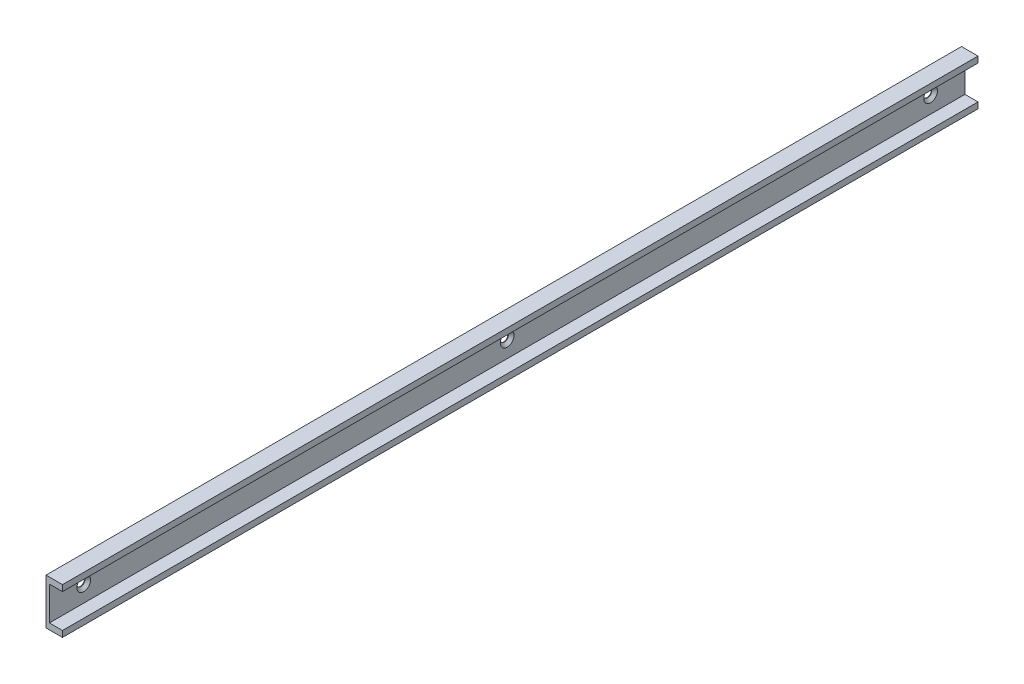
SolidWorks part; units mm, degrees
material "6061 合金"
ref_plane "前视基准面" through (0, 0, 0) normal (0, 0, 1) x (1, 0, 0)
ref_plane "上视基准面" through (0, 0, 0) normal (0, 1, 0) x (1, 0, 0)
ref_plane "右视基准面" through (0, 0, 0) normal (1, 0, 0) x (0, 0, -1)
sketch "草图1" plane through (0, 0, 0) normal (0, 0, 1) x (1, 0, 0)
  line L1 (-3.6, -10) -> (3.6, -10)
  line L2 (-3.6, -10) -> (-3.6, 10)
  line L3 (-3.6, 10) -> (3.6, 10)
  line L4 (3.6, -10) -> (3.6, 10)
  line L5 (0, 10) -> (0, -10) construction
  line L6 (-3.6, 0) -> (3.6, 0) construction
  point P0 (0, 0)
  dimension "D1" = 20
  dimension "D2" = 7.2
extrude "凸台-拉伸1" add sketch "草图1" along normal mid plane 400
sketch "草图2" plane through (0, 0, 0) normal (0, 0, 1) x (1, 0, 0)
  line L0 (3.6, 7.35) -> (-2.1, 7.35)
  line L1 (3.6, -10) -> (3.6, 10) construction
  line L2 (-2.1, 7.35) -> (-2.1, -7.35)
  line L3 (-2.1, -7.35) -> (3.6, -7.35)
  line L4 (3.6, -7.35) -> (3.6, 7.35)
  line L5 (0, 0) -> (3.6, 0) construction
  line L6 (-3.6, 10) -> (-3.6, -10) construction
  dimension "D1" = 14.7
  dimension "D2" = 1.5
extrude "切除-拉伸1" cut sketch "草图2" against normal mid plane 400
sketch "草图4" plane through (0, 0, 0) normal (0, 0, 1) x (1, 0, 0)
  line L0 (-3.6, 1.75) -> (-3.35, 1.75)
  line L1 (-3.6, 10) -> (-3.6, -10) construction
  line L2 (-3.35, 1.75) -> (-2.1, 3)
  line L3 (-2.1, 7.35) -> (-2.1, -7.35) construction
  line L4 (-2.1, 3) -> (-2.1, 0)
  line L5 (-2.1, 0) -> (-3.6, 0)
  line L6 (-3.6, 0) -> (-3.6, 1.75)
  dimension "D1" = 1.75
  dimension "D2" = 45
  dimension "D3" = 3
revolve "切除-旋转1" cut sketch "草图4" angle 360 about L5
pattern_linear "阵列(线性)1" count 2 spacing 185 along (0, 0, -1) count 2 spacing 185 along (0, 0, 1) of "切除-旋转1"
